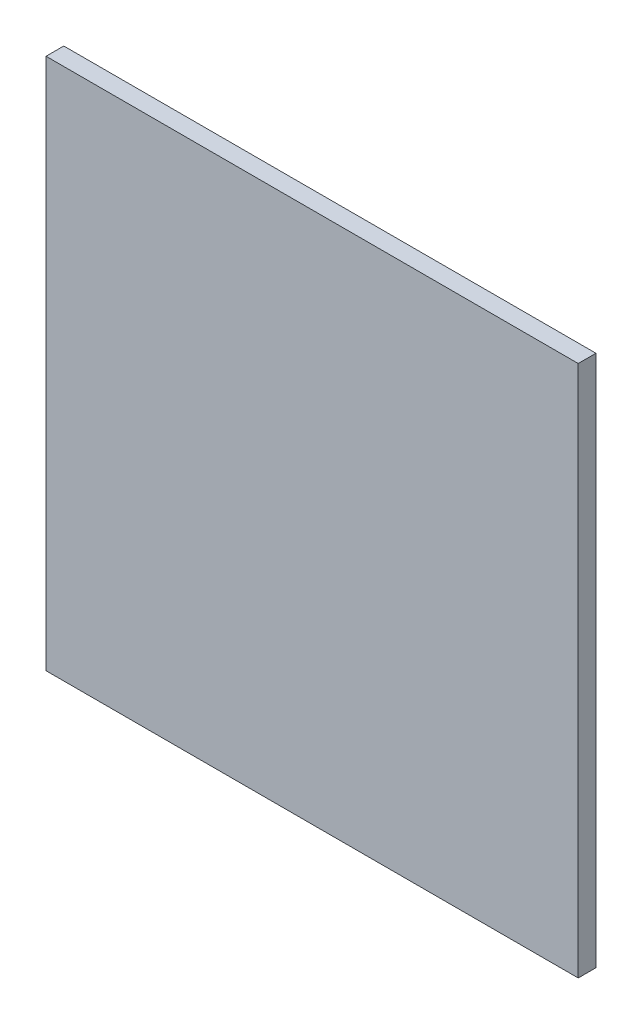
SolidWorks part; units mm, degrees
ref_plane "Front Plane" through (0, 0, 0) normal (0, 0, 1) x (1, 0, 0)
ref_plane "Top Plane" through (0, 0, 0) normal (0, 1, 0) x (1, 0, 0)
ref_plane "Right Plane" through (0, 0, 0) normal (1, 0, 0) x (0, 0, -1)
sketch "Sketch1" plane through (0, 0, 0) normal (0, 0, 1) x (1, 0, 0)
  line L1 (-151.1046, 93.2253) -> (148.8954, 93.2253)
  line L2 (-151.1046, 93.2253) -> (-151.1046, -206.7747)
  line L3 (-151.1046, -206.7747) -> (148.8954, -206.7747)
  line L4 (148.8954, 93.2253) -> (148.8954, -206.7747)
  dimension "D1" = 300
  dimension "D2" = 300
extrude "Boss-Extrude1" add sketch "Sketch1" along normal blind 10
